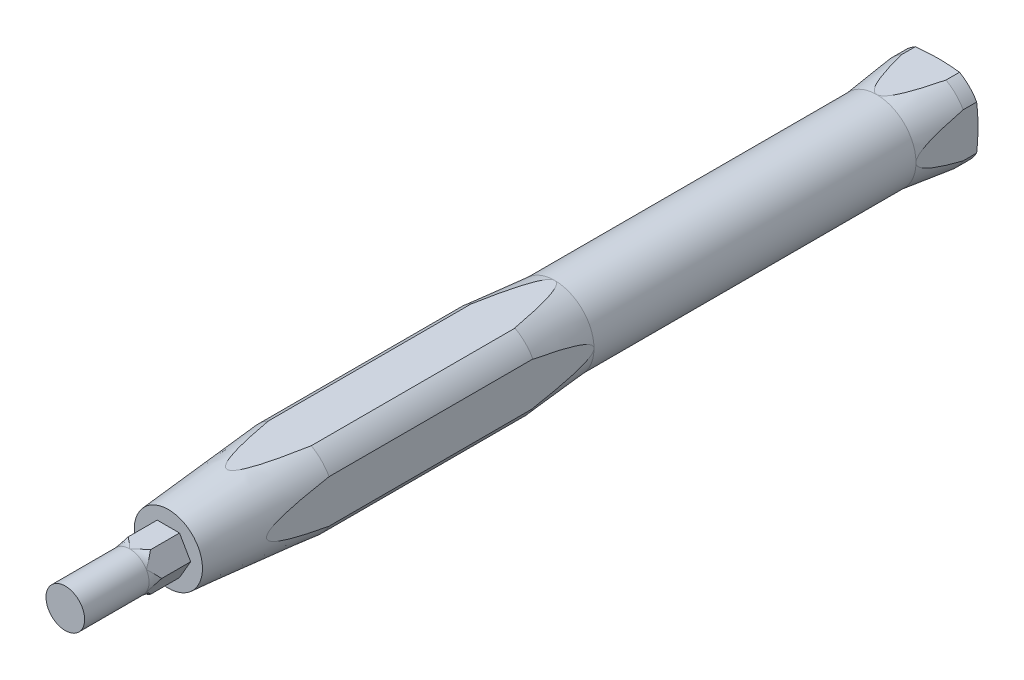
SolidWorks part; units mm, degrees
ref_plane "Front" through (0, 0, 0) normal (0, 0, 1) x (1, 0, 0)
ref_plane "Top" through (0, 0, 0) normal (0, 1, 0) x (1, 0, 0)
ref_plane "Right" through (0, 0, 0) normal (1, 0, 0) x (0, 0, -1)
sketch "Sketch1" plane through (0, 0, 0) normal (0, 0, 1) x (1, 0, 0)
  line L1 (-6.1, 6.1) -> (6.1, 6.1)
  line L2 (-6.1, 6.1) -> (-6.1, -6.1)
  line L3 (-6.1, -6.1) -> (6.1, -6.1)
  line L4 (6.1, 6.1) -> (6.1, -6.1)
  line L5 (0, -6.1) -> (0, 6.1) construction
  line L6 (-6.1, 0) -> (6.1, 0) construction
  point P0 (0, 0)
  dimension "D1" = 12.2
extrude "Boss-Extrude1" add sketch "Sketch1" along normal blind 120
sketch "Sketch2" plane through (0, 0, 120) normal (0, 0, 1) x (1, 0, 0)
  circle A0 centre (0, 0) radius 6.95
  dimension "D1" = 13.9
extrude "Cut-Extrude1" cut sketch "Sketch2" against normal through all flip side to cut
sketch "Sketch3" plane through (0, 0, 120) normal (0, 0, 1) x (1, 0, 0)
  circle A0 centre (0, 0) radius 5.3
  dimension "D1" = 10.6
extrude "Cut-Extrude2" cut sketch "Sketch3" against normal blind 20 draft 5 flip side to cut
sketch "Sketch4" plane through (0, 0, 120) normal (0, 0, 1) x (1, 0, 0)
  circle A0 centre (0, 0) radius 6.1
  dimension "D1" = 12.2
extrude "Cut-Extrude3" cut sketch "Sketch4" against normal blind 50 from offset 60 flip side to cut offset against normal yes
sketch "Sketch5" plane through (0, 0, 60) normal (0, 0, -1) x (-1, 0, 0)
  circle A1 centre (0, 0) radius 6.1
  circle A2 centre (0, 0) radius 6.1
  dimension "D1" = 0
extrude "Cut-Extrude4" cut sketch "Sketch5" against normal blind 9.5 draft 5 flip side to cut
sketch "Sketch7" plane through (0, 0, 0) normal (0, 0, -1) x (-1, 0, 0)
  line L0 (3.3305, -6.1) -> (-3.3305, -6.1) construction
  line L1 (6.1, 3.3305) -> (6.1, -3.3305) construction
  line L2 (-3.3305, 6.1) -> (3.3305, 6.1) construction
  line L3 (-6.1, -3.3305) -> (-6.1, 3.3305) construction
  line L4 (3.4337, -6.1) -> (-3.4337, -6.1)
  line L5 (6.1, 3.4337) -> (6.1, -3.4337)
  line L6 (-3.4337, 6.1) -> (3.4337, 6.1)
  line L7 (-6.1, -3.4337) -> (-6.1, 3.4337)
  arc A0 (-3.4337, 6.1) -> (-6.1, 3.4337) centre (0, 0) ccw
  arc A1 (6.1, 3.4337) -> (3.4337, 6.1) centre (0, 0) ccw
  arc A2 (3.4337, -6.1) -> (6.1, -3.4337) centre (0, 0) ccw
  arc A3 (-6.1, -3.4337) -> (-3.4337, -6.1) centre (0, 0) ccw
  point P11 (-5.6326, -6.1)
  point P13 (-6.1, -4.7693)
  point P15 (-6.1, 4.8044)
  point P17 (-4.3966, 6.1)
  point P19 (5.5332, 6.1)
  point P21 (6.1, 4.5462)
  point P23 (6.1, -4.7693)
  point P25 (5.1271, -6.1)
  dimension "D1" = 14
extrude "Boss-Extrude2" add sketch "Sketch7" against normal blind 3.5
sketch "Sketch6" plane through (0, 0, 10) normal (0, 0, 1) x (1, 0, 0)
  circle A1 centre (0, 0) radius 6.1
  circle A2 centre (0, 0) radius 6.1
  dimension "D1" = 0
extrude "Cut-Extrude6" cut sketch "Sketch6" against normal blind 9.5 draft 7 flip side to cut
sketch "Sketch8" plane through (0, 0, 0) normal (0, 0, -1) x (-1, 0, 0)
  circle A0 centre (0, 0) radius 4.5
  dimension "D1" = 9
extrude "Cut-Extrude7" cut sketch "Sketch8" against normal blind 3.5 draft 77 flip side to cut
sketch "Sketch9" plane through (0, 0, 120) normal (0, 0, 1) x (1, 0, 0)
  line L1 (1.7321, 3) -> (-1.7321, 3)
  line L2 (-1.7321, 3) -> (-3.4641, 0)
  line L3 (-3.4641, 0) -> (-1.7321, -3)
  line L4 (-1.7321, -3) -> (1.7321, -3)
  line L5 (1.7321, -3) -> (3.4641, 0)
  line L6 (3.4641, 0) -> (1.7321, 3)
  circle A0 centre (0, 0) radius 3 construction
  dimension "D1" = 6
extrude "Boss-Extrude3" add sketch "Sketch9" along normal blind 16
sketch "Sketch10" plane through (0, 0, 0) normal (0, 1, 0) x (1, 0, 0)
  line L0 (3, -136) -> (3, -126)
  line L1 (3.4641, -136) -> (1.7321, -136) construction
  line L2 (3.4641, -136) -> (3.4641, -120) construction
  line L3 (3.4641, -124.5) -> (3.4641, -136)
  line L4 (3.4641, -136) -> (3, -136)
  line L5 (0, -101.1404) -> (0, -120) construction
  arc A0 (3, -126) -> (3.4641, -124.5) centre (5.6561, -126) cw
  point P12 (3.4641, -124.4421)
  dimension "D1" = 3
  dimension "D2" = 1.5
  dimension "D3" = 10
revolve "Cut-Revolve1" cut sketch "Sketch10" angle 360 about axis through (0, 0, 120) along (0, 0, -1)
